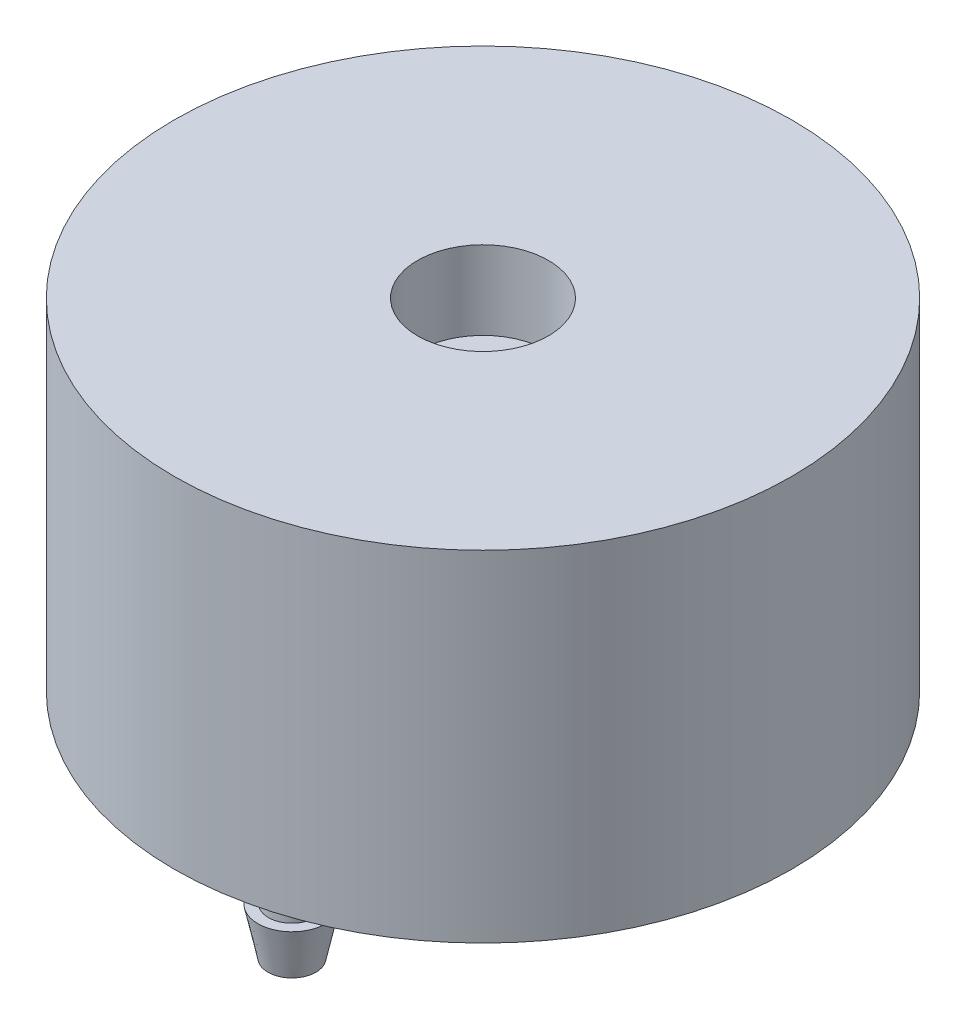
SolidWorks part; units mm, degrees
ref_plane "Plan de face" through (0, 0, 0) normal (0, 0, 1) x (1, 0, 0)
ref_plane "Plan de dessus" through (0, 0, 0) normal (0, 1, 0) x (1, 0, 0)
ref_plane "Plan de droite" through (0, 0, 0) normal (1, 0, 0) x (0, 0, -1)
sketch "Esquisse1" plane through (0, 0, 0) normal (0, 1, 0) x (1, 0, 0)
  circle A0 centre (0, 0) radius 5.9
  dimension "D1" = 11.8
extrude "Boss.-Extru.1" add sketch "Esquisse1" along normal blind 5
shell "Coque1" thickness 0.5
sketch "Esquisse2" plane through (0, 5, 0) normal (0, 1, 0) x (1, 0, 0)
  circle A0 centre (0, 0) radius 5.9
  circle A1 centre (0, 0) radius 1.25
  dimension "D1" = 11.8
  dimension "D2" = 2.5
extrude "Boss.-Extru.2" add sketch "Esquisse2" along normal blind 1.5
sketch "Esquisse3" plane through (0, 0.5, 0) normal (0, 1, 0) x (1, 0, 0)
  circle A0 centre (0, 0) radius 4.5
  dimension "D1" = 9
extrude "Boss.-Extru.3" add sketch "Esquisse3" along normal blind 4
sketch "Esquisse4" plane through (0, 0, 0) normal (0, -1, 0) x (1, 0, 0)
  line L0 (0, 5.9) -> (0, -5.9) construction
  circle A0 centre (0, 0) radius 5.9 construction
  circle A1 centre (0, 3.65) radius 0.45
  circle A2 centre (0, -3.647) radius 0.45
  dimension "D1" = 0.9
  dimension "D2" = 0.9
  dimension "D3" = 2.25
  dimension "D4" = 2.253
extrude "Boss.-Extru.4" add sketch "Esquisse4" along normal blind 2.6
ref_plane "Plan1" through (0, -1.7, 0) normal (0, 1, 0) x (1, 0, 0)
sketch "Esquisse5" plane through (0, -1.7, 0) normal (0, 1, 0) x (1, 0, 0)
  circle A0 centre (0, -3.65) radius 0.65
  circle A1 centre (0, 3.647) radius 0.65
  dimension "D1" = 1.3
  dimension "D2" = 1.3
extrude "Boss.-Extru.5" add sketch "Esquisse5" against normal blind 0.9 draft 12
